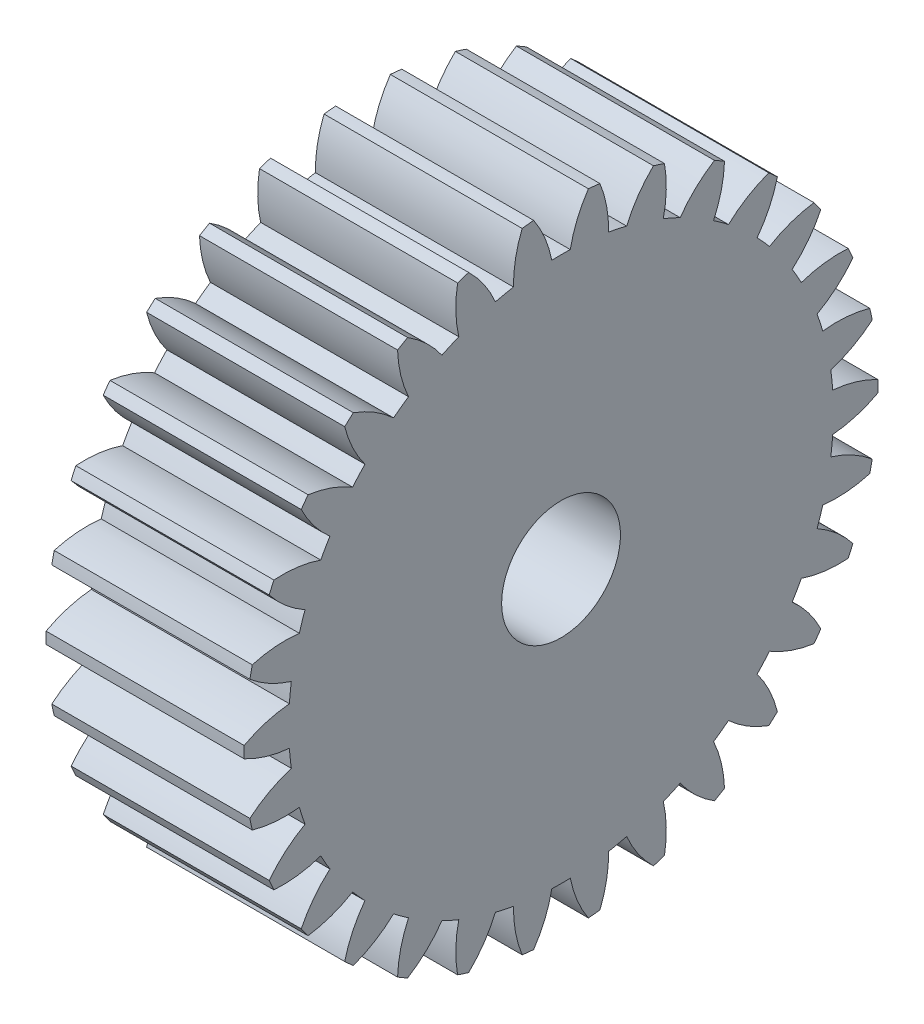
SolidWorks part; units mm, degrees
ref_plane "Plane1" through (0, 0, 0) normal (0, 0, 1) x (1, 0, 0)
ref_plane "Plane2" through (0, 0, 0) normal (0, 1, 0) x (1, 0, 0)
ref_plane "Plane3" through (0, 0, 0) normal (1, 0, 0) x (0, 0, -1)
sketch "HoldingSke" plane through (0, 0, 0) normal (0, 1, 0) x (1, 0, 0)
  line L0 (0, 0) -> (1.7321, -1)
  line L1 (-15, 0) -> (100, 0) construction
  line L2 (0, 0) -> (-2.1039, 2.3779)
  line L3 (0, 0) -> (-11.863, 4.5341)
  line L4 (0, 0) -> (7.479, 4.318)
  line L5 (0, 0) -> (-46.8476, -17.4728)
  line L6 (0, 0) -> (-4.1448, -2.7965)
  line L7 (-2.1039, 2.3779) -> (8.6586, 51.2059)
  line L8 (-76.2, 54.61) -> (-75.7, 54.61)
  line L9 (-71.009, 38.7566) -> (-53.1078, 45.2721)
  line L10 (-76.2, 71.12) -> (104.1128, 71.12)
  line L11 (0, 0) -> (-5, 0)
  line L12 (-76.2, 101.6) -> (-76.181, 101.6)
  line L13 (24.9733, 27.94) -> (52.9518, 28.4284)
  line L14 (24.9733, 27.94) -> (24.9743, 27.94)
  line L15 (24.9733, 27.94) -> (100.4006, 29.5858)
  line L16 (-63.627, -0.5) -> (-12.827, -0.5)
  circle A0 centre (0, 0) radius 1.5
  circle A1 centre (0, 0) radius 6.874
  circle A2 centre (0, 0) radius 37.5
  circle A3 centre (0, 0) radius 1.5
  dimension "MHD" = 13.748
  dimension "Hub_dia" = 75
  dimension "Bore" = 3
  dimension "MBD" = 3
  dimension "Num_teeth" = 30
  dimension "Pitch" = 2
  dimension "Overall_len" = 50
  dimension "Show_teeth" = 30
  dimension "Thickness" = 5
  dimension "OAL" = 50.0001
  dimension "T_dim" = 0.5
  dimension "Ap" = 20
  dimension "H" = 19.05
  dimension "Pitch_radius" = 180.3128
  dimension "Width" = 5
  dimension "Backlash" = 0.019
  dimension "Addendum_fac" = 1
  dimension "Dedendum_fac" = 1.25
  dimension "Clearance_fac" = 0.25
  dimension "Dedendum_add" = 0.001
  dimension "Module" = 0.5
sketch "BasProSke" plane through (0, 0, 0) normal (0, 1, 0) x (1, 0, 0)
  line L0 (-10, 0) -> (60, 0) construction
  line L1 (0, 0) -> (0, 8)
  line L2 (0, 0) -> (5, 0)
  line L3 (5, 0) -> (5, 8)
  line L4 (5, 8) -> (0, 8)
  dimension "Thickness" = 5
  dimension "Diameter" = 16
revolve "Base-Revolve" add sketch "BasProSke" angle 360 about L0
sketch "TooCutSke" plane through (0, 0, 0) normal (1, 0, 0) x (0, 0, -1)
  line L1 (0, 0) -> (0, 107) construction
  line L2 (0, 0) -> (-0.4258, 7.4879) construction
  line L3 (0, 0) -> (-1.5661, 14.9007) construction
  line L4 (-0.4258, 7.4879) -> (-0.7831, 7.4504) construction
  arc A0 (0.2331, 6.87) -> (-0.2331, 6.87) centre (0, 0) ccw
  arc A1 (0.707, 7.9942) -> (-0.707, 7.9942) centre (0, 0) ccw
  circle A2 centre (0, 0) radius 7.5 construction
  circle A3 centre (0, 0) radius 7.0477 construction
  arc A4 (-0.2331, 6.87) -> (-0.707, 7.9942) centre (-3.1767, 6.2911) ccw
  arc A5 (0.707, 7.9942) -> (0.2331, 6.87) centre (3.1767, 6.2911) ccw
  dimension "Root_dia" = 13.748
  dimension "Overcut_dia" = 16.0508
  dimension "Pitch_dia" = 15
  dimension "Base_dia" = 14.0954
  dimension "Flank_rad" = 3
  dimension "Half_ang" = 6
  dimension "Half_CT" = 0.3593
extrude "ToothCut" cut sketch "TooCutSke" along normal through all
fillet "Breaks" [suppressed] radius 0.01
fillet "RootFillets" [suppressed] radius 0.126
pattern_circular "TeethCuts" count 30 every 12 about axis through (-10, 0, 0) along (1, 0, 0) of "ToothCut", "RootFillets", "Breaks"
sketch "HubNeaOneSke" plane through (0, 0, 0) normal (-1, 0, 0) x (0, 0, 1)
  circle A0 centre (0, 0) radius 6.874
  dimension "Diameter" = 13.748
extrude "HubNearOne" [suppressed] add sketch "HubNeaOneSke" along normal blind 45.0001
sketch "HubNeaBotSke" plane through (0, 0, 0) normal (-1, 0, 0) x (0, 0, 1)
  circle A0 centre (0, 0) radius 6.874
  dimension "Diameter" = 13.748
extrude "HubNearBoth" [suppressed] add sketch "HubNeaBotSke" along normal blind 22.5
ref_plane "FarPln" through (5, 0, 0) normal (1, 0, 0) x (0, 0, -1)
sketch "HubFarSke" plane through (5, 0, 0) normal (1, 0, 0) x (0, 0, -1)
  circle A0 centre (0, 0) radius 6.874
  dimension "Diameter" = 13.748
extrude "HubFar" [suppressed] add sketch "HubFarSke" along normal blind 22.5
sketch "BorSke" plane through (0, 0, 0) normal (1, 0, 0) x (0, 0, -1)
  circle A0 centre (0, 0) radius 1.5
  dimension "Diameter" = 3
extrude "Bore" cut sketch "BorSke" along normal mid plane 100.0001
sketch "KeySke" plane through (0, 0, 0) normal (1, 0, 0) x (0, 0, -1)
  line L0 (-0.6, 0) -> (-0.6, 2)
  line L1 (-0.6, 2) -> (0.6, 2)
  line L2 (0.6, 2) -> (0.6, 0)
  line L3 (0, 0) -> (0, 34) construction
  line L4 (-0.6, 0) -> (0.6, 0)
  dimension "Offset" = 2
  dimension "Width" = 1.2
extrude "Keyway" [suppressed] cut sketch "KeySke" along normal mid plane 100.0001
pattern_circular "Keyway2" [suppressed] count 2 every 90 about axis through (-10, 0, 0) along (1, 0, 0)
equation "' \"Module@HoldingSke\" = 6.35"
equation "' \"Num_teeth@HoldingSke\" = 12"
equation "' \"Ap@HoldingSke\" =  20"
equation "' \"Ap@HoldingSke\" = 20"
equation "' \"Width@HoldingSke\" = 0.5 * 25.4"
equation "' \"Hub_dia@HoldingSke\"= 1 * 25.4"
equation "' \"Hub_dia@HoldingSke\" = 1 * 25.4"
equation "' \"Overall_len@HoldingSke\" = 1.0 * 25.4"
equation "' \"Bore@HoldingSke\" = 0.75 * 25.4"
equation "' \"T_dim@HoldingSke\" = 0.1 * 25.4"
equation "' \"Width@KeySke\" = 0.25 * 25.4"
equation "' \"Show_teeth@HoldingSke\" = 13"
equation "' \"Backlash@HoldingSke\" = 0.009 * 25.4"
equation "' \"Addendum_fac@HoldingSke\" = 1.0"
equation "' \"Dedendum_fac@HoldingSke\" = 1.25"
equation "' \"Dedendum_add@HoldingSke\" = 0.00005 * 25.4"
equation "' \"Clearance_fac@HoldingSke\" = 0.25"
equation "\"Pitch@HoldingSke\" = 1 / \"Module@HoldingSke\""
equation "\"Overcut_dia@TooCutSke\" = (\"Num_teeth@HoldingSke\" + 2 * \"Addendum_fac@HoldingSke\") / \"Pitch@HoldingSke\" + 0.002 * 25.4"
equation "\"Pitch_dia@TooCutSke\" = \"Num_teeth@HoldingSke\" / \"Pitch@HoldingSke\""
equation "\"Base_dia@TooCutSke\" = \"Num_teeth@HoldingSke\" / \"Pitch@HoldingSke\" * cos((\"Ap@HoldingSke\"  * 3.14159265 / 180))"
equation "\"Root_dia@TooCutSke\" = (\"Num_teeth@HoldingSke\" + 2) / \"Pitch@HoldingSke\" - 2 * (\"Addendum_fac@HoldingSke\" + \"Dedendum_fac@HoldingSke\") / \"Pitch@HoldingSke\" - \"Dedendum_add@HoldingSke\" * 2"
equation "\"Half_ang@TooCutSke\" = 180 / \"Num_teeth@HoldingSke\""
equation "\"Half_CT@TooCutSke\" = \"Num_teeth@HoldingSke\" / \"Pitch@HoldingSke\" * sin((3.14159265 / 2 / \"Num_teeth@HoldingSke\")) / 2 - 7 * \"Backlash@HoldingSke\" / 4"
equation "\"Flank_rad@TooCutSke\" = \"Num_teeth@HoldingSke\" / \"Pitch@HoldingSke\" / 5"
equation "\"Radius@RootFillets\" = \"Clearance_fac@HoldingSke\" / \"Pitch@HoldingSke\" + \"Dedendum_add@HoldingSke\""
equation "\"Break_rad@Breaks\" = 0.02 / \"Pitch@HoldingSke\""
equation "\"Thickness@HoldingSke\" = \"Width@HoldingSke\""
equation "\"OAL@HoldingSke\" = \"Thickness@HoldingSke\""
equation "\"MHD@HoldingSke\" = (\"Num_teeth@HoldingSke\" + 2) / \"Pitch@HoldingSke\" - 2 * (\"Addendum_fac@HoldingSke\" + \"Dedendum_fac@HoldingSke\")  / \"Pitch@HoldingSke\" - \"Dedendum_add@HoldingSke\" * 2"
equation "\"MBD@HoldingSke\" = (\"Num_teeth@HoldingSke\" + 2) / \"Pitch@HoldingSke\" - 2 * (\"Addendum_fac@HoldingSke\" + \"Dedendum_fac@HoldingSke\")  / \"Pitch@HoldingSke\" - \"Dedendum_add@HoldingSke\" * 2 - 0.002 * 25.4"
equation "\"MHD@HoldingSke\" = ((sgn( \"MHD@HoldingSke\" - \"Hub_dia@HoldingSke\" )-1)*( \"MHD@HoldingSke\" - \"Hub_dia@HoldingSke\" ))/-2+ \"Hub_dia@HoldingSke\""
equation "\"MBD@HoldingSke\" = ((sgn( \"MBD@HoldingSke\" - \"Bore@HoldingSke\" )-1)*( \"MBD@HoldingSke\" - \"Bore@HoldingSke\" ))/-2+ \"Bore@HoldingSke\""
equation "\"OAL@HoldingSke\" = ((sgn( \"OAL@HoldingSke\" - \"Overall_len@HoldingSke\" )+1)*( \"OAL@HoldingSke\" - \"Overall_len@HoldingSke\" ))/2 + \"Overall_len@HoldingSke\" + 0.000002 * 25.4"
equation "\"Num_teeth@TeethCuts\" = int( \"Show_teeth@HoldingSke\" ) + 1"
equation "\"Num_teeth@TeethCuts\" = ((sgn( \"Num_teeth@TeethCuts\" - \"Num_teeth@HoldingSke\" )-1)*( \"Num_teeth@TeethCuts\" - \"Num_teeth@HoldingSke\" ))/-2+ \"Num_teeth@HoldingSke\""
equation "\"Num_teeth@TeethCuts\" = ((sgn( \"Num_teeth@TeethCuts\" - 2.0)+1)*( \"Num_teeth@TeethCuts\" - 2.0))/2 +2.0"
equation "\"Angle@TeethCuts\" = 360.0 / \"Num_teeth@HoldingSke\""
equation "\"Diameter@BasProSke\" = (\"Num_teeth@HoldingSke\" + 2 * \"Addendum_fac@HoldingSke\") / \"Pitch@HoldingSke\""
equation "\"Thickness@BasProSke\"  = \"Thickness@HoldingSke\""
equation "' \"Fillet_rad@BasProSke\" =  \"Thickness@HoldingSke\" * 0.05"
equation "' \"Fillet_rad@BasProSke\" = \"Thickness@HoldingSke\" * 0.05"
equation "\"MHD@HoldingSke\" = ((sgn( \"MHD@HoldingSke\" - \"Root_dia@TooCutSke\" )-1)*( \"MHD@HoldingSke\" - \"Root_dia@TooCutSke\" ))/-2+ \"Root_dia@TooCutSke\""
equation "\"Diameter@HubNeaOneSke\" = \"MHD@HoldingSke\""
equation "\"Length@HubNearOne\" = \"OAL@HoldingSke\" - \"Thickness@BasProSke\""
equation "\"Diameter@HubNeaBotSke\" = \"MHD@HoldingSke\""
equation "\"Length@HubNearBoth\" = ( \"OAL@HoldingSke\" - \"Thickness@BasProSke\" ) / 2.0"
equation "\"Thickness@FarPln\" = \"Thickness@BasProSke\""
equation "\"Diameter@HubFarSke\" = \"MHD@HoldingSke\""
equation "\"Length@HubFar\" = ( \"OAL@HoldingSke\" - \"Thickness@BasProSke\" ) / 2.0"
equation "\"Diameter@BorSke\" = \"MBD@HoldingSke\""
equation "\"D1@Bore\" = \"OAL@HoldingSke\" * 2.0"
equation "\"D1@Keyway\" = \"OAL@HoldingSke\" * 2.0"
equation "\"Offset@KeySke\" = \"T_dim@HoldingSke\" + \"MBD@HoldingSke\" / 2.0"
